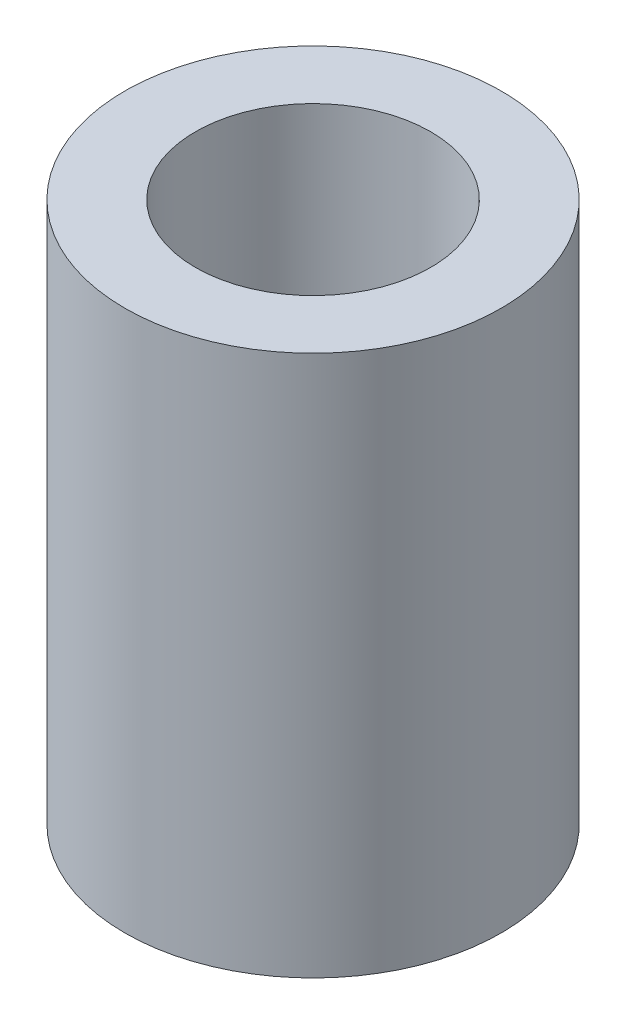
SolidWorks part; units mm, degrees
ref_plane "Front" through (0, 0, 0) normal (0, 0, 1) x (1, 0, 0)
ref_plane "Top" through (0, 0, 0) normal (0, 1, 0) x (1, 0, 0)
ref_plane "Right" through (0, 0, 0) normal (1, 0, 0) x (0, 0, -1)
sketch "Sketch1" plane through (0, 0, 0) normal (0, 1, 0) x (1, 0, 0)
  circle A0 centre (0, 0) radius 5
  circle A1 centre (0, 0) radius 8
  dimension "D1" = 10
  dimension "D2" = 3
extrude "Boss-Extrude1" add sketch "Sketch1" along normal blind 23
